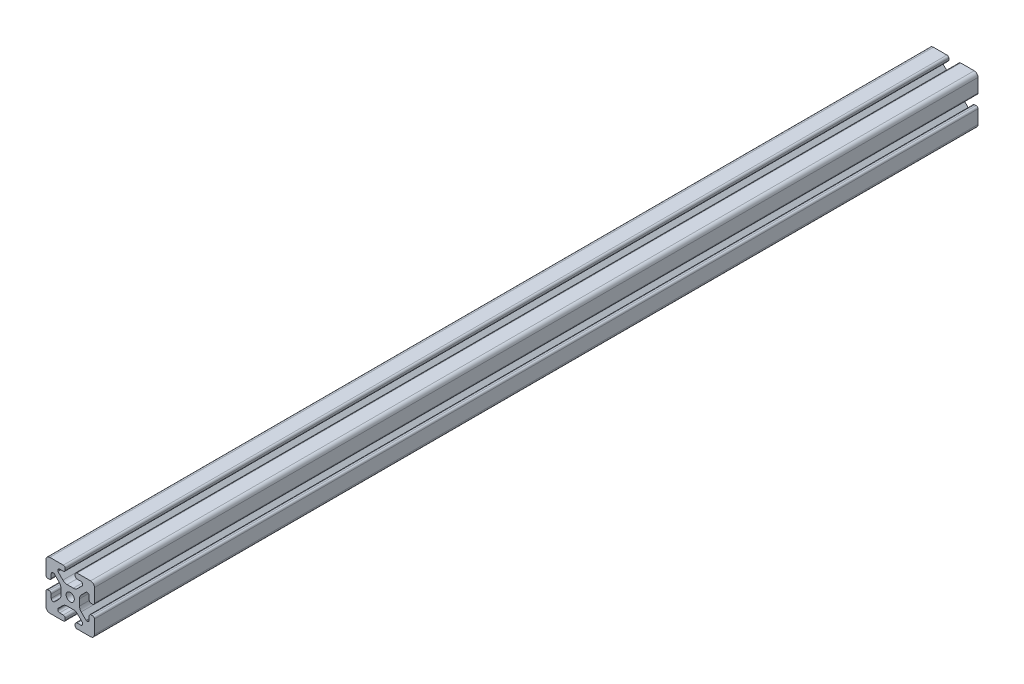
SolidWorks part; units mm, degrees
ref_plane "Front Plane" through (0, 0, 0) normal (0, 0, 1) x (1, 0, 0)
ref_plane "Top Plane" through (0, 0, 0) normal (0, 1, 0) x (1, 0, 0)
ref_plane "Right Plane" through (0, 0, 0) normal (1, 0, 0) x (0, 0, -1)
ref_plane "Plane1" through (0, 0, -4000) normal (0, 0, -1) x (-1, 0, 0)
sketch "Sketch1" plane through (0, 0, -4000) normal (0, 0, -1) x (-1, 0, 0)
  line L0 (16.83, 20) -> (5.6904, 20)
  line L1 (4.1204, 18.43) -> (4.1204, 17.25)
  line L2 (5.6904, 15.68) -> (8.7154, 15.68)
  line L3 (10.2854, 14.11) -> (10.2854, 13.6549)
  line L4 (10.0628, 13.1175) -> (6.0551, 9.1098)
  line L5 (2.6153, 7.685) -> (-2.6153, 7.685)
  line L6 (-6.0551, 9.1098) -> (-10.0628, 13.1175)
  line L7 (-10.2854, 13.6549) -> (-10.2854, 14.11)
  line L8 (-8.7154, 15.68) -> (-5.6904, 15.68)
  line L9 (-4.1204, 17.25) -> (-4.1204, 18.43)
  line L10 (-5.6904, 20) -> (-16.83, 20)
  line L11 (-20, 16.83) -> (-20, 5.6904)
  line L12 (-18.43, 4.1204) -> (-17.25, 4.1204)
  line L13 (-15.68, 5.6904) -> (-15.68, 8.7154)
  line L14 (-14.11, 10.2854) -> (-13.6549, 10.2854)
  line L15 (-13.1175, 10.0628) -> (-9.1098, 6.0551)
  line L16 (-7.685, 2.6153) -> (-7.685, -2.6153)
  line L17 (-9.1098, -6.0551) -> (-13.1175, -10.0628)
  line L18 (-13.6549, -10.2854) -> (-14.11, -10.2854)
  line L19 (-15.68, -8.7154) -> (-15.68, -5.6904)
  line L20 (-17.25, -4.1204) -> (-18.43, -4.1204)
  line L21 (-20, -5.6904) -> (-20, -16.83)
  line L22 (-16.83, -20) -> (-5.6904, -20)
  line L23 (-4.1204, -18.43) -> (-4.1204, -17.25)
  line L24 (-5.6904, -15.68) -> (-8.7154, -15.68)
  line L25 (-10.2854, -14.11) -> (-10.2854, -13.6549)
  line L26 (-10.0628, -13.1175) -> (-6.0551, -9.1098)
  line L27 (-2.6153, -7.685) -> (2.6153, -7.685)
  line L28 (6.0551, -9.1098) -> (10.0628, -13.1175)
  line L29 (10.2854, -13.6549) -> (10.2854, -14.11)
  line L30 (8.7154, -15.68) -> (5.6904, -15.68)
  line L31 (4.1204, -17.25) -> (4.1204, -18.43)
  line L32 (5.6904, -20) -> (16.83, -20)
  line L33 (20, -16.83) -> (20, -5.6904)
  line L34 (18.43, -4.1204) -> (17.25, -4.1204)
  line L35 (15.68, -5.6904) -> (15.68, -8.7154)
  line L36 (14.11, -10.2854) -> (13.6549, -10.2854)
  line L37 (13.1175, -10.0628) -> (9.1098, -6.0551)
  line L38 (7.685, -2.6153) -> (7.685, 2.6153)
  line L39 (9.1098, 6.0551) -> (13.1175, 10.0628)
  line L40 (13.6549, 10.2854) -> (14.11, 10.2854)
  line L41 (15.68, 8.7154) -> (15.68, 5.6904)
  line L42 (17.25, 4.1204) -> (18.43, 4.1204)
  line L43 (20, 5.6904) -> (20, 16.83)
  circle A0 centre (0, 0) radius 3.4
  arc A1 (20, 16.83) -> (16.83, 20) centre (16.83, 16.83) ccw
  arc A2 (5.6904, 20) -> (4.1204, 18.43) centre (5.6904, 18.43) ccw
  arc A3 (4.1204, 17.25) -> (5.6904, 15.68) centre (5.6904, 17.25) ccw
  arc A4 (8.7154, 15.68) -> (10.2854, 14.11) centre (8.7154, 14.11) cw
  arc A5 (10.2854, 13.6549) -> (10.0628, 13.1175) centre (9.5254, 13.6549) cw
  arc A6 (6.0551, 9.1098) -> (2.6153, 7.685) centre (2.6153, 12.5496) cw
  arc A7 (-2.6153, 7.685) -> (-6.0551, 9.1098) centre (-2.6153, 12.5496) cw
  arc A8 (-10.0628, 13.1175) -> (-10.2854, 13.6549) centre (-9.5254, 13.6549) cw
  arc A9 (-10.2854, 14.11) -> (-8.7154, 15.68) centre (-8.7154, 14.11) cw
  arc A10 (-5.6904, 15.68) -> (-4.1204, 17.25) centre (-5.6904, 17.25) ccw
  arc A11 (-4.1204, 18.43) -> (-5.6904, 20) centre (-5.6904, 18.43) ccw
  arc A12 (-16.83, 20) -> (-20, 16.83) centre (-16.83, 16.83) ccw
  arc A13 (-20, 5.6904) -> (-18.43, 4.1204) centre (-18.43, 5.6904) ccw
  arc A14 (-17.25, 4.1204) -> (-15.68, 5.6904) centre (-17.25, 5.6904) ccw
  arc A15 (-15.68, 8.7154) -> (-14.11, 10.2854) centre (-14.11, 8.7154) cw
  arc A16 (-13.6549, 10.2854) -> (-13.1175, 10.0628) centre (-13.6549, 9.5254) cw
  arc A17 (-9.1098, 6.0551) -> (-7.685, 2.6153) centre (-12.5496, 2.6153) cw
  arc A18 (-7.685, -2.6153) -> (-9.1098, -6.0551) centre (-12.5496, -2.6153) cw
  arc A19 (-13.1175, -10.0628) -> (-13.6549, -10.2854) centre (-13.6549, -9.5254) cw
  arc A20 (-14.11, -10.2854) -> (-15.68, -8.7154) centre (-14.11, -8.7154) cw
  arc A21 (-15.68, -5.6904) -> (-17.25, -4.1204) centre (-17.25, -5.6904) ccw
  arc A22 (-18.43, -4.1204) -> (-20, -5.6904) centre (-18.43, -5.6904) ccw
  arc A23 (-20, -16.83) -> (-16.83, -20) centre (-16.83, -16.83) ccw
  arc A24 (-5.6904, -20) -> (-4.1204, -18.43) centre (-5.6904, -18.43) ccw
  arc A25 (-4.1204, -17.25) -> (-5.6904, -15.68) centre (-5.6904, -17.25) ccw
  arc A26 (-8.7154, -15.68) -> (-10.2854, -14.11) centre (-8.7154, -14.11) cw
  arc A27 (-10.2854, -13.6549) -> (-10.0628, -13.1175) centre (-9.5254, -13.6549) cw
  arc A28 (-6.0551, -9.1098) -> (-2.6153, -7.685) centre (-2.6153, -12.5496) cw
  arc A29 (2.6153, -7.685) -> (6.0551, -9.1098) centre (2.6153, -12.5496) cw
  arc A30 (10.0628, -13.1175) -> (10.2854, -13.6549) centre (9.5254, -13.6549) cw
  arc A31 (10.2854, -14.11) -> (8.7154, -15.68) centre (8.7154, -14.11) cw
  arc A32 (5.6904, -15.68) -> (4.1204, -17.25) centre (5.6904, -17.25) ccw
  arc A33 (4.1204, -18.43) -> (5.6904, -20) centre (5.6904, -18.43) ccw
  arc A34 (16.83, -20) -> (20, -16.83) centre (16.83, -16.83) ccw
  arc A35 (20, -5.6904) -> (18.43, -4.1204) centre (18.43, -5.6904) ccw
  arc A36 (17.25, -4.1204) -> (15.68, -5.6904) centre (17.25, -5.6904) ccw
  arc A37 (15.68, -8.7154) -> (14.11, -10.2854) centre (14.11, -8.7154) cw
  arc A38 (13.6549, -10.2854) -> (13.1175, -10.0628) centre (13.6549, -9.5254) cw
  arc A39 (9.1098, -6.0551) -> (7.685, -2.6153) centre (12.5496, -2.6153) cw
  arc A40 (7.685, 2.6153) -> (9.1098, 6.0551) centre (12.5496, 2.6153) cw
  arc A41 (13.1175, 10.0628) -> (13.6549, 10.2854) centre (13.6549, 9.5254) cw
  arc A42 (14.11, 10.2854) -> (15.68, 8.7154) centre (14.11, 8.7154) cw
  arc A43 (15.68, 5.6904) -> (17.25, 4.1204) centre (17.25, 5.6904) ccw
  arc A44 (18.43, 4.1204) -> (20, 5.6904) centre (18.43, 5.6904) ccw
extrude "Boss-Extrude1" add sketch "Sketch1" against normal blind 4000
ref_plane "Plane2" through (0, 0, -730) normal (0, 0, 1) x (1, 0, 0)
sketch "Sketch2" plane through (0, 0, -730) normal (0, 0, 1) x (1, 0, 0)
  line L1 (-35.4045, 45.1725) -> (49.1351, 45.1725)
  line L2 (-35.4045, 45.1725) -> (-35.4045, -53.5162)
  line L3 (-35.4045, -53.5162) -> (49.1351, -53.5162)
  line L4 (49.1351, 45.1725) -> (49.1351, -53.5162)
extrude "Cut-Extrude1" cut sketch "Sketch2" against normal through all
